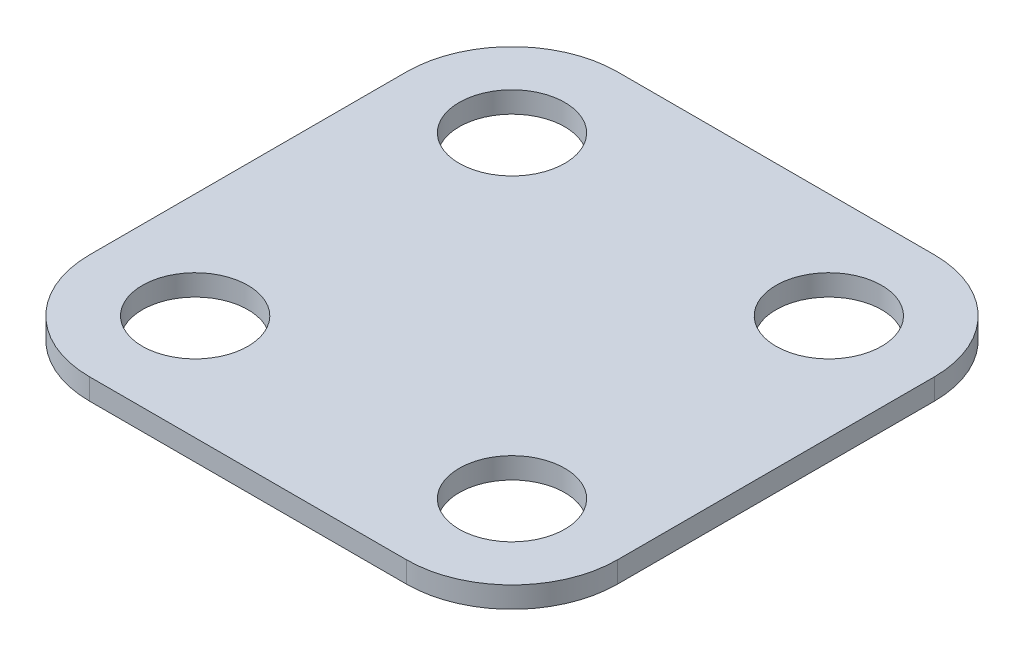
SolidWorks part; units mm, degrees
material "Guma"
ref_plane "Płaszczyzna przednia" through (0, 0, 0) normal (0, 0, 1) x (1, 0, 0)
ref_plane "Płaszczyzna górna" through (0, 0, 0) normal (0, 1, 0) x (1, 0, 0)
ref_plane "Płaszczyzna prawa" through (0, 0, 0) normal (1, 0, 0) x (0, 0, -1)
sketch "Szkic1" plane through (0, 0, 0) normal (0, 1, 0) x (1, 0, 0)
  line L1 (-15, 25) -> (15, 25)
  line L2 (-25, 15) -> (-25, -15)
  line L3 (-15, -25) -> (15, -25)
  line L4 (25, 15) -> (25, -15)
  line L5 (-25, 25) -> (25, -25) construction
  line L6 (-25, -25) -> (25, 25) construction
  arc A0 (-15, 25) -> (-25, 15) centre (-15, 15) ccw
  arc A1 (-25, -15) -> (-15, -25) centre (-15, -15) ccw
  arc A2 (15, -25) -> (25, -15) centre (15, -15) ccw
  arc A3 (15, 25) -> (25, 15) centre (15, 15) cw
  circle A4 centre (15, 15) radius 5
  circle A5 centre (15, -15) radius 5
  circle A6 centre (-15, -15) radius 5
  circle A7 centre (-15, 15) radius 5
  point P0 (0, 0)
  point P29 (0, 0)
  dimension "D1" = 10
  dimension "D2" = 10
  dimension "D4" = 50
  dimension "D3" = 4
extrude "Dodanie-wyciągnięcie1" add sketch "Szkic1" against normal blind 2
